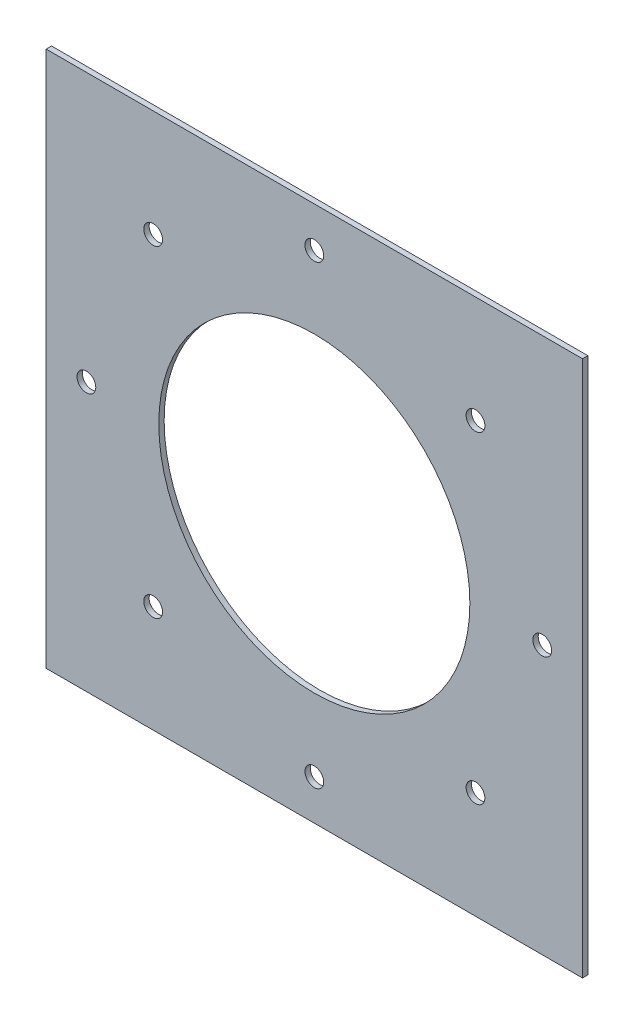
SolidWorks part; units mm, degrees
ref_plane "前视基准面" through (0, 0, 0) normal (0, 0, 1) x (1, 0, 0)
ref_plane "上视基准面" through (0, 0, 0) normal (0, 1, 0) x (1, 0, 0)
ref_plane "右视基准面" through (0, 0, 0) normal (1, 0, 0) x (0, 0, -1)
sketch "草图1" plane through (0, 0, 0) normal (0, 0, 1) x (1, 0, 0)
  line L1 (-50, -50) -> (50, -50)
  line L2 (-50, -50) -> (-50, 50)
  line L3 (-50, 50) -> (50, 50)
  line L4 (50, -50) -> (50, 50)
  line L5 (-50, -50) -> (50, 50) construction
  line L6 (-50, 50) -> (50, -50) construction
  point P0 (0, 0)
  dimension "D1" = 100
  dimension "D2" = 100
extrude "凸台-拉伸1" add sketch "草图1" along normal blind 1
sketch "草图2" plane through (0, 0, 1) normal (0, 0, 1) x (1, 0, 0)
  circle A0 centre (0, 0) radius 42.5 construction
  circle A1 centre (-42.5, 0) radius 1.75
  circle A2 centre (-30.052, 30.052) radius 1.75
  circle A3 centre (0, 42.5) radius 1.75
  circle A4 centre (30.052, 30.052) radius 1.75
  circle A5 centre (42.5, 0) radius 1.75
  circle A6 centre (30.052, -30.052) radius 1.75
  circle A7 centre (0, -42.5) radius 1.75
  circle A8 centre (-30.052, -30.052) radius 1.75
  point P22 (0, 0)
  dimension "D1" = 85
  dimension "D2" = 3.5
  dimension "D3" = 8
extrude "切除-拉伸1" cut sketch "草图2" against normal blind 4
sketch "草图3" plane through (0, 0, 1) normal (0, 0, 1) x (1, 0, 0)
  circle A0 centre (0, 0) radius 29
  dimension "D1" = 58
extrude "切除-拉伸2" cut sketch "草图3" against normal blind 4
